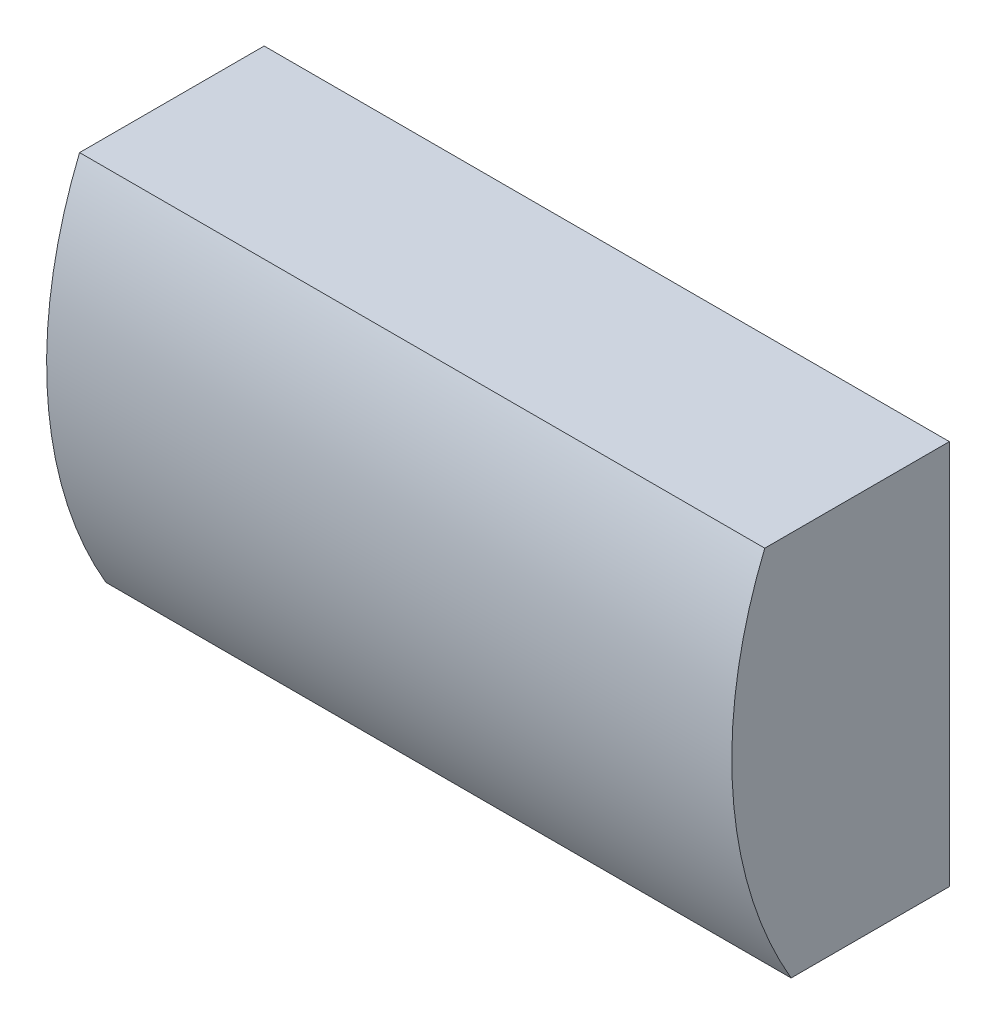
SolidWorks part; units mm, degrees
ref_plane "Front Plane" through (0, 0, 0) normal (0, 0, 1) x (1, 0, 0)
ref_plane "Top Plane" through (0, 0, 0) normal (0, 1, 0) x (1, 0, 0)
ref_plane "Right Plane" through (0, 0, 0) normal (1, 0, 0) x (0, 0, -1)
sketch "Sketch1" plane through (0, 0, 0) normal (0, 0, 1) x (1, 0, 0)
  line L1 (-44.5455, 19.3939) -> (35.4545, 19.3939)
  line L2 (-44.5455, 19.3939) -> (-44.5455, -25.6061)
  line L3 (-44.5455, -25.6061) -> (35.4545, -25.6061)
  line L4 (35.4545, 19.3939) -> (35.4545, -25.6061)
  dimension "D1" = 80
  dimension "D2" = 45
extrude "Boss-Extrude1" add sketch "Sketch1" along normal blind 25.4
sketch "Sketch2" plane through (-44.5455, 0, 0) normal (-1, 0, 0) x (0, 0, 1)
  line L0 (0, 0) -> (-25.4, 0)
  circle A0 centre (-25.4, 0) radius 50.8
  circle A1 centre (-25.4, 0) radius 84.6233
  line M2 (0, -25.6061) -> (25.4, -25.6061)
  line M3 (25.4, -25.6061) -> (25.4, 19.3939)
  line M4 (25.4, 19.3939) -> (0, 19.3939)
  dimension "D2" = 101.6
  dimension "D1" = 25.4
extrude "Cut-Extrude5" cut sketch "Sketch2" against normal blind 101.6 contours A0 M3 M4 | A0 M2 M3
